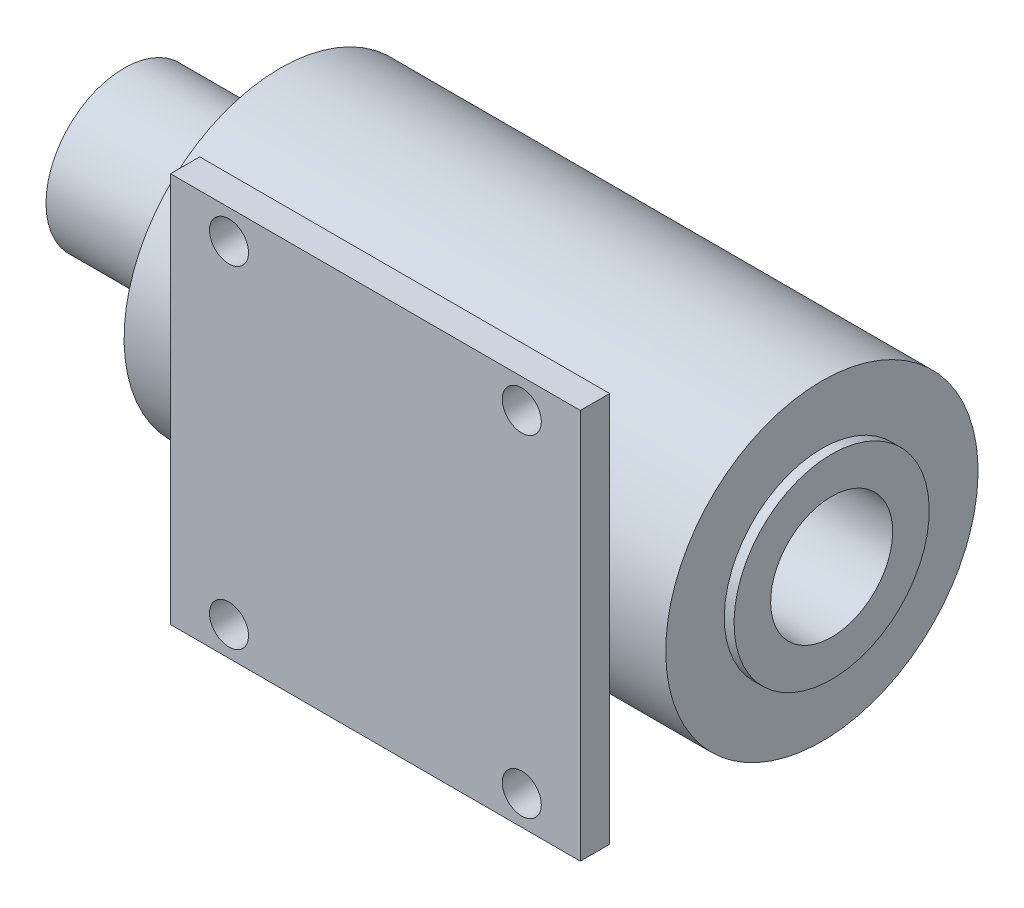
SolidWorks part; units mm, degrees
ref_plane "Front" through (0, 0, 0) normal (0, 0, 1) x (1, 0, 0)
ref_plane "Top" through (0, 0, 0) normal (0, 1, 0) x (1, 0, 0)
ref_plane "Right" through (0, 0, 0) normal (1, 0, 0) x (0, 0, -1)
sketch "Sketch1" plane through (0, 0, 0) normal (0, 0, 1) x (1, 0, 0)
  line L0 (24.8204, 11.0941) -> (24.8204, -5.9059) construction
  line L1 (-11.1796, 14.0941) -> (30.8204, 14.0941)
  line L2 (-11.1796, 14.0941) -> (-11.1796, -25.9059)
  line L3 (-11.1796, -25.9059) -> (30.8204, -25.9059)
  line L4 (30.8204, 14.0941) -> (30.8204, -25.9059)
  line L5 (30.8204, -5.9059) -> (-11.1796, -5.9059) construction
  line L6 (24.8204, -22.9059) -> (24.8204, -5.9059) construction
  line L7 (9.8204, 14.0941) -> (9.8204, -25.9059) construction
  line L8 (-5.1796, 11.0941) -> (9.8204, 11.0941) construction
  line L9 (24.8204, 11.0941) -> (9.8204, 11.0941) construction
  circle A0 centre (-5.1796, 11.0941) radius 2
  circle A1 centre (-5.1796, -22.9059) radius 2
  circle A2 centre (24.8204, 11.0941) radius 2
  circle A3 centre (24.8204, -22.9059) radius 2
  dimension "D1" = 30
  dimension "D3" = 4
  dimension "D4" = 34
  dimension "D2" = 42
  dimension "D5" = 40
extrude "Boss-Extrude1" add sketch "Sketch1" along normal blind 3
ref_plane "Plane1" through (8.8204, 0, 0) normal (1, 0, 0) x (0, 0, -1)
sketch "Sketch2" plane through (8.8204, 0, 0) normal (1, 0, 0) x (0, 0, -1)
  line L0 (9.6582, 15.1013) -> (9.6582, -24.7857) construction
  line L1 (0, -5.9059) -> (28.6565, -5.9059) construction
  line L2 (0, -25.9059) -> (0, 14.0941) construction
  line L3 (-3, -25.9059) -> (-3, 14.0941) construction
  circle A0 centre (16, -5.9059) radius 16
  dimension "D1" = 32
  dimension "D2" = 19
extrude "Boss-Extrude2" add sketch "Sketch2" along normal blind 27.75 and the other way blind 27.75 separate body
sketch "Sketch3" plane through (-18.9296, 0, 0) normal (-1, 0, 0) x (0, 0, 1)
  circle A0 centre (-16, -5.9059) radius 8
  dimension "D1" = 16
extrude "Boss-Extrude3" add sketch "Sketch3" along normal blind 16
sketch "Sketch4" plane through (36.5704, 0, 0) normal (1, 0, 0) x (0, 0, -1)
  circle A0 centre (16, -5.9059) radius 10
  dimension "D1" = 20
extrude "Boss-Extrude4" add sketch "Sketch4" along normal blind 1
sketch "Sketch5" plane through (37.5704, 0, 0) normal (1, 0, 0) x (0, 0, -1)
  circle A0 centre (16, -5.9059) radius 6.25
  dimension "D1" = 12.5
extrude "Cut-Extrude1" cut sketch "Sketch5" against normal blind 51
sketch "Sketch6" plane through (-13.4296, 0, 0) normal (1, 0, 0) x (0, 0, -1)
  circle A0 centre (16, -5.9059) radius 2.3813
  dimension "D1" = 4.7625
extrude "Cut-Extrude2" cut sketch "Sketch6" against normal through all
